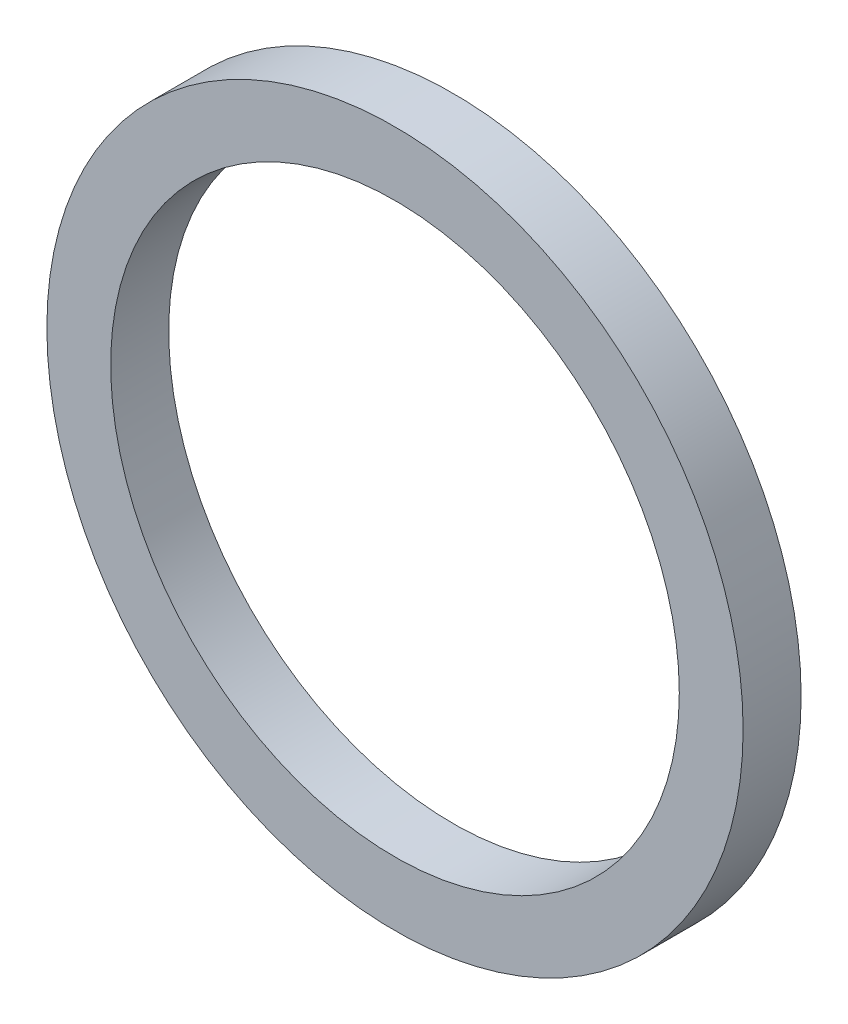
SolidWorks part; units mm, degrees
ref_plane "Front Plane" through (0, 0, 0) normal (0, 0, 1) x (1, 0, 0)
ref_plane "Top Plane" through (0, 0, 0) normal (0, 1, 0) x (1, 0, 0)
ref_plane "Right Plane" through (0, 0, 0) normal (1, 0, 0) x (0, 0, -1)
sketch "Sketch1" plane through (0, 0, 0) normal (0, 0, 1) x (1, 0, 0)
  circle A0 centre (0, 0) radius 19.05
  circle A1 centre (0, 0) radius 15.5575
  dimension "D1" = 38.1
  dimension "D2" = 31.115
extrude "Boss-Extrude1" add sketch "Sketch1" along normal mid plane 3.175
